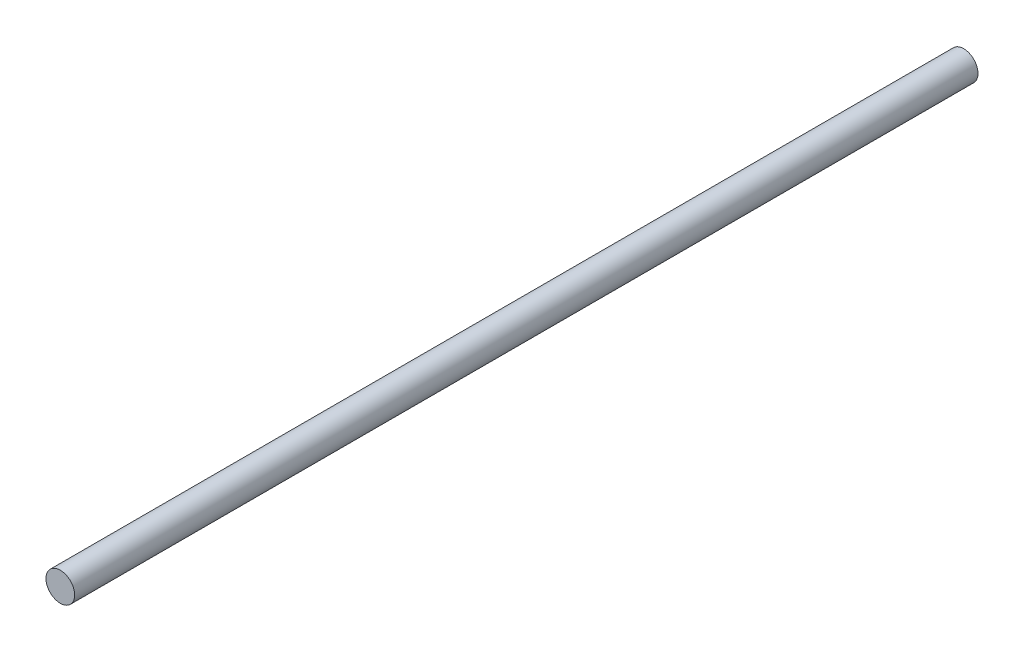
SolidWorks part; units mm, degrees
ref_plane "Front Plane" through (0, 0, 0) normal (0, 0, 1) x (1, 0, 0)
ref_plane "Top Plane" through (0, 0, 0) normal (0, 1, 0) x (1, 0, 0)
ref_plane "Right Plane" through (0, 0, 0) normal (1, 0, 0) x (0, 0, -1)
sketch "Sketch1" plane through (0, 0, 0) normal (0, 0, 1) x (1, 0, 0)
  circle A0 centre (0, 0) radius 1.5875
  dimension "D1" = 3.175
extrude "Boss-Extrude1" add sketch "Sketch1" along normal mid plane 100
